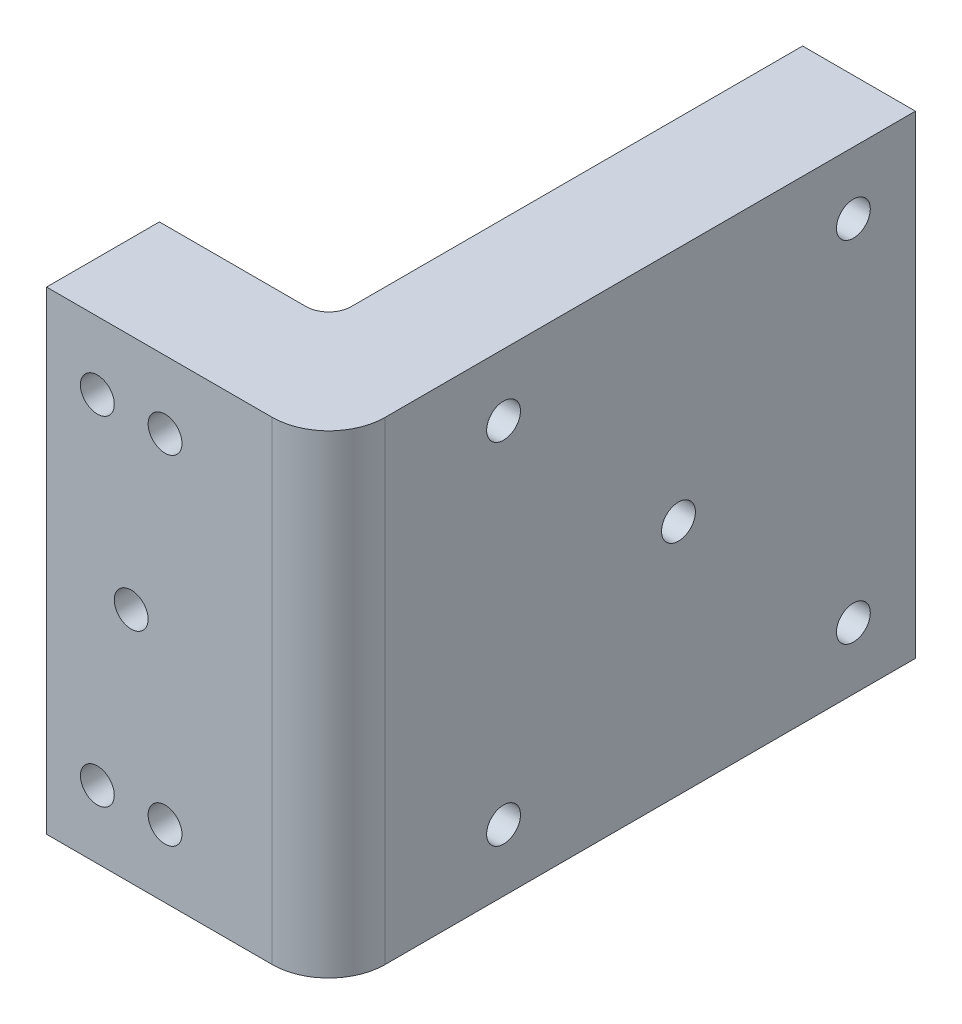
SolidWorks part; units mm, degrees
ref_plane "前视基准面" through (0, 0, 0) normal (0, 0, 1) x (1, 0, 0)
ref_plane "上视基准面" through (0, 0, 0) normal (0, 1, 0) x (1, 0, 0)
ref_plane "右视基准面" through (0, 0, 0) normal (1, 0, 0) x (0, 0, -1)
sketch "草图1" plane through (0, 0, 0) normal (0, 0, 1) x (1, 0, 0)
  line L0 (-3, 21) -> (-3, 9.3052) construction
  line L1 (-7.5, 21) -> (7.5, 21)
  line L2 (-7.5, 21) -> (-7.5, -21)
  line L3 (-7.5, -21) -> (7.5, -21)
  line L4 (7.5, 21) -> (7.5, -21)
  line L5 (-7.5, 21) -> (7.5, -21) construction
  line L6 (-7.5, -21) -> (7.5, 21) construction
  line L7 (3, 20.6054) -> (3, 10.357) construction
  line L9 (7.5, 21) -> (17.5, 21)
  line L10 (7.5, 21) -> (7.5, -21)
  line L11 (7.5, -21) -> (17.5, -21)
  line L12 (17.5, 21) -> (17.5, -21)
  circle A0 centre (-3, 15) radius 1.5
  circle A2 centre (-3, -15) radius 1.5
  circle A4 centre (3, 15) radius 1.5
  circle A6 centre (3, -15) radius 1.5
  circle A7 centre (0, 0) radius 1.5
  point P0 (0, 0)
  point P6 (-3, 21)
  point P7 (-3, 21)
  point P8 (3, 21)
  dimension "D5" = 3
  dimension "D8" = 3
  dimension "D1" = 15
  dimension "D2" = 42
  dimension "D3" = 4.5
  dimension "D4" = 4.5
  dimension "D6" = 6
  dimension "D7" = 6
  dimension "D9" = 10
extrude "凸台-拉伸1" add sketch "草图1" along normal blind 10 contours L4 L1 L2 L3 A7 A6 A4 A2 A0 | L12 L9 L4 L11
sketch "草图2" plane through (0, 0, 0) normal (0, 0, -1) x (-1, 0, 0)
  line L0 (7.5, 21) -> (-7.5, 21) construction
  line L1 (7.5, 21) -> (7.5, -21) construction
  line L2 (7.5, -21) -> (-7.5, -21) construction
  line L3 (-7.5, 21) -> (-7.5, -21) construction
  line L4 (-7.5, 21) -> (-7.5, -21) construction
  line L5 (-7.5, 21) -> (-17.5, 21) construction
  line L6 (-17.5, 21) -> (-17.5, -21) construction
  line L7 (-7.5, -21) -> (-17.5, -21) construction
  line L8 (7.5, 21) -> (-7.5, 21)
  line L9 (7.5, 21) -> (7.5, -21)
  line L10 (7.5, -21) -> (-7.5, -21)
  line L11 (-7.5, 21) -> (-7.5, -21)
  line L12 (-7.5, 21) -> (-7.5, -21)
  line L13 (-7.5, 21) -> (-17.5, 21)
  line L14 (-17.5, 21) -> (-17.5, -21)
  line L15 (-7.5, -21) -> (-17.5, -21)
  line L17 (-17.5, 21) -> (-7.5, 21)
  line L18 (-17.5, 21) -> (-17.5, -21)
  line L19 (-17.5, -21) -> (-7.5, -21)
  line L20 (-7.5, 21) -> (-7.5, -21)
  circle A1 centre (3, 15) radius 1.5
  circle A2 centre (3, 15) radius 1.5
  circle A3 centre (0, 0) radius 1.5
  circle A4 centre (0, 0) radius 1.5
  circle A5 centre (-3, -15) radius 1.5
  circle A6 centre (-3, -15) radius 1.5
  circle A7 centre (-3, 15) radius 1.5
  circle A8 centre (-3, 15) radius 1.5
  circle A9 centre (3, -15) radius 1.5
  circle A10 centre (3, -15) radius 1.5
  line M11 (-17.5, -21) -> (7.5, -21)
  line M13 (7.5, 21) -> (-17.5, 21)
  line M14 (-17.5, 21) -> (-17.5, -21)
  dimension "D1" = 0
  dimension "D2" = 0
  dimension "D3" = 0
  dimension "D4" = 0
  dimension "D5" = 0
extrude "凸台-拉伸2" add sketch "草图2" along normal blind 42 contours L11 M13 M14 M11
sketch "草图3" plane through (7.5, 0, 0) normal (-1, 0, 0) x (0, 0, 1)
  line L2 (-42, 21) -> (0, -21) construction
  line L3 (-42, -21) -> (0, -21) construction
  line L4 (0, 21) -> (-42, -21) construction
  line L5 (10, -21) -> (0, -21) construction
  circle A0 centre (-36.5, 15.5) radius 1.5
  circle A1 centre (-5.5, 15.5) radius 1.5
  circle A2 centre (-36.5, -15.5) radius 1.5
  circle A3 centre (-5.5, -15.5) radius 1.5
  circle A4 centre (-21, 0) radius 1.5
  dimension "D3" = 3
  dimension "D6" = 3
  dimension "D1" = 31
extrude "切除-拉伸1" cut sketch "草图3" against normal blind 15
fillet "圆角1" radius 2 1 edges at (7.5, 0, 0)
fillet "圆角2" radius 5 1 edges at (17.5, 0, 10)
